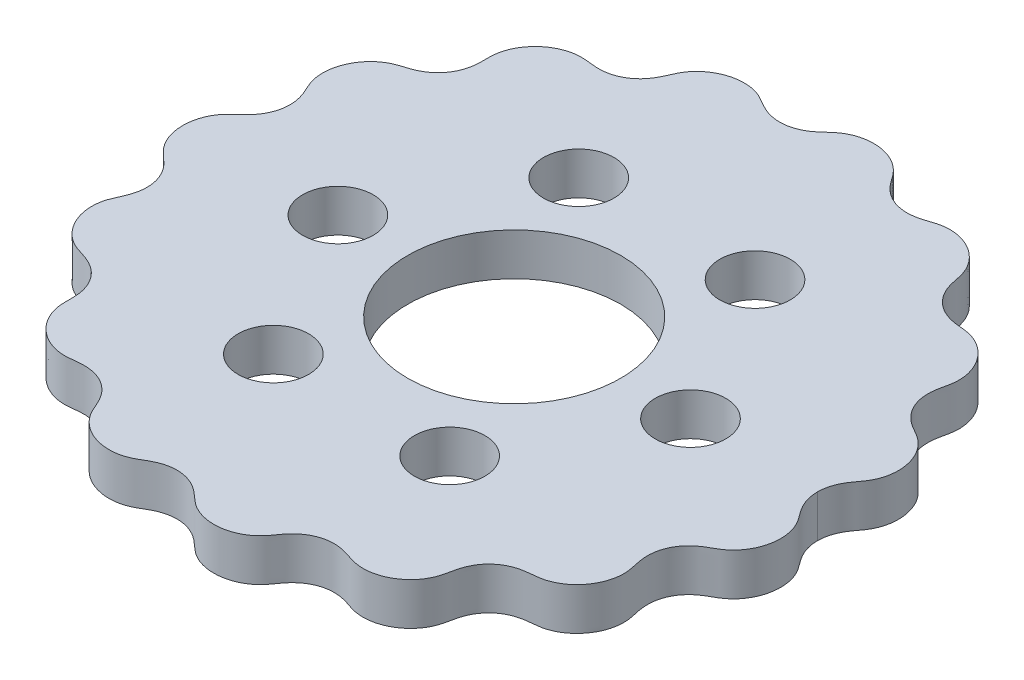
SolidWorks part; units mm, degrees
ref_plane "Alzado" through (0, 0, 0) normal (0, 0, 1) x (1, 0, 0)
ref_plane "Planta" through (0, 0, 0) normal (0, 1, 0) x (1, 0, 0)
ref_plane "Vista lateral" through (0, 0, 0) normal (1, 0, 0) x (0, 0, -1)
sketch "Croquis1" plane through (0, 0, 0) normal (0, 1, 0) x (1, 0, 0)
  line L1 (-23.5, 0) -> (21.5, 0) construction
  circle A8 centre (0, 0) radius 12.5 construction
  circle A9 centre (12.5, 0) radius 2.5
  circle A10 centre (6.25, -10.8253) radius 2.5
  circle A11 centre (-6.25, -10.8253) radius 2.5
  circle A12 centre (-12.5, 0) radius 2.5
  circle A13 centre (-6.25, 10.8253) radius 2.5
  circle A14 centre (6.25, 10.8253) radius 2.5
  circle A15 centre (0, 0) radius 7.55
  spline S0 degree 4 poles (22.3938, 6.206) (22.5098, 6.0505) (22.7166, 5.7207) (22.9456, 5.1865) (23.0698, 4.5223) (23.0708, 3.9491) (22.995, 3.4431) (22.8861, 3.0677) (22.7402, 2.7346) (22.5701, 2.4451) (22.4166, 2.2248) (22.255, 2.0106) (22.0968, 1.7938) (21.9608, 1.5854) (21.8481, 1.3858) (21.7364, 1.1545) (21.6505, 0.933) (21.5836, 0.7054) (21.5367, 0.4716) (21.5147, 0.3126) (21.5037, 0.1561) (21.4997, 0.0354) (21.4998, -0.0402) (21.5033, -0.1416) (21.5104, -0.2506) (21.521, -0.3535) (21.5352, -0.4522) (21.5572, -0.575) (21.5906, -0.7229) (21.6393, -0.8925) (21.7079, -1.082) (21.7887, -1.2667) (21.8884, -1.4605) (22.0086, -1.6616) (22.1498, -1.8685) (22.3094, -2.0824) (22.4687, -2.2964) (22.6163, -2.5189) (22.7773, -2.8114) (22.9505, -3.2395) (23.0755, -3.8173) (23.0785, -4.5347) (22.9117, -5.2906) (22.61, -5.9374) (22.2185, -6.4567) (21.7772, -6.8519) (21.3209, -7.1251) (20.8, -7.4026) (20.2753, -7.7948) (19.8063, -8.3446) (19.475, -9.0614) (19.3598, -9.7832) (19.4098, -10.4522) (19.5346, -10.9747) (19.6222, -11.3739) (19.6633, -11.7809) (19.6552, -12.251) (19.5391, -12.8416) (19.2523, -13.5076) (18.7937, -14.1364) (18.2622, -14.6034) (17.7101, -14.9167) (17.1699, -15.1) (16.67, -15.1754) (16.1916, -15.2048) (15.7411, -15.2785) (15.3268, -15.3998) (14.9543, -15.5661) (14.5264, -15.8332) (14.0827, -16.2428) (13.7242, -16.7761) (13.514, -17.344) (13.4123, -17.8049) (13.3351, -18.2081) (13.2359, -18.6074) (13.025, -19.1081) (12.6416, -19.6627) (12.1028, -20.1652) (11.4122, -20.5639) (10.7076, -20.7793) (10.0356, -20.834) (9.4966, -20.7664) (9.1011, -20.6526) (8.7134, -20.5178) (8.2633, -20.3754) (7.6664, -20.2735) (7.0253, -20.3174) (6.4487, -20.4968) (6.0035, -20.7338) (5.6732, -20.9733) (5.361, -21.2715) (5.0719, -21.6247) (4.8073, -22.0244) (4.4921, -22.4196) (4.0632, -22.7958) (3.5158, -23.1172) (2.8456, -23.344) (2.0718, -23.4267) (1.3515, -23.3422) (0.7822, -23.1473) (0.3707, -22.9196) (0.0947, -22.7199) (-0.1125, -22.543) (-0.3613, -22.3108) (-0.71, -21.9972) (-1.2072, -21.6575) (-1.8903, -21.3967) (-2.6764, -21.325) (-3.3872, -21.4564) (-3.9891, -21.7146) (-4.49, -22.027) (-4.9546, -22.2856) (-5.5176, -22.4702) (-6.163, -22.5495) (-6.8743, -22.4875) (-7.6119, -22.2539) (-8.2323, -21.8928) (-8.7188, -21.4502) (-9.0744, -20.9697) (-9.3045, -20.4864) (-9.5278, -19.9281) (-9.8701, -19.3468) (-10.3865, -18.8074) (-11.0945, -18.3987) (-11.8197, -18.2212) (-12.4943, -18.2154) (-13.0895, -18.3011) (-13.623, -18.3435) (-14.217, -18.2758) (-14.8436, -18.0758) (-15.4665, -17.719) (-16.0376, -17.197) (-16.447, -16.612) (-16.701, -16.0135) (-16.8226, -15.4336) (-16.8309, -14.902) (-16.8108, -14.312) (-16.8881, -13.6616) (-17.1298, -12.9803) (-17.5849, -12.3353) (-18.1524, -11.8742) (-18.6951, -11.6135) (-19.1411, -11.4683) (-19.4666, -11.3689) (-19.7233, -11.2779) (-20.0342, -11.1388) (-20.4373, -10.8962) (-20.8907, -10.5007) (-21.3241, -9.9191) (-21.6393, -9.2077) (-21.778, -8.5138) (-21.7733, -7.8791) (-21.6621, -7.3195) (-21.4771, -6.849) (-21.2186, -6.3289) (-21.0011, -5.7035) (-20.9214, -4.968) (-21.0454, -4.2657) (-21.2856, -3.7121) (-21.5436, -3.3243) (-21.7592, -3.0674) (-21.974, -2.8515) (-22.1775, -2.6683) (-22.3844, -2.489) (-22.5845, -2.3019) (-22.7693, -2.0995) (-22.9352, -1.8813) (-23.0967, -1.6229) (-23.2446, -1.3222) (-23.3437, -1.0477) (-23.4069, -0.8089) (-23.4413, -0.6387) (-23.4581, -0.5412) (-23.4757, -0.42) (-23.4911, -0.2795) (-23.5008, -0.0674) (-23.501, 0.0617) (-23.4905, 0.2958) (-23.4696, 0.4722) (-23.4384, 0.6634) (-23.3968, 0.8485) (-23.3447, 1.0319) (-23.2823, 1.2119) (-23.2033, 1.4023) (-23.1053, 1.6016) (-22.952, 1.8603) (-22.7243, 2.166) (-22.4073, 2.4773) (-22.0362, 2.7842) (-21.7134, 3.1099) (-21.3864, 3.5349) (-21.0986, 4.0919) (-20.9508, 4.7107) (-20.9589, 5.3479) (-21.0451, 5.768) (-21.1059, 5.9731) (-21.1402, 6.0744) knots 0 0 0 0 0 0.008384 0.016767 0.0249 0.028966 0.033032 0.038829 0.041728 0.044627 0.047525 0.050424 0.053322 0.056221 0.05827 0.060319 0.064418 0.066467 0.068516 0.070566 0.07159 0.072615 0.073703 0.074791 0.075879 0.076967 0.078055 0.079143 0.081319 0.083495 0.085672 0.087848 0.090024 0.092906 0.095787 0.098669 0.101551 0.104433 0.107315 0.113078 0.12144 0.129802 0.138039 0.146276 0.152005 0.157733 0.163462 0.169191 0.177517 0.185843 0.194348 0.202854 0.208734 0.214615 0.217555 0.220495 0.226376 0.23487 0.243365 0.251552 0.25974 0.265182 0.270624 0.276066 0.281508 0.285899 0.29029 0.294681 0.299071 0.307626 0.316181 0.322096 0.325053 0.328011 0.333925 0.33984 0.348384 0.356927 0.365471 0.374015 0.37993 0.385844 0.388802 0.391759 0.397674 0.406229 0.414784 0.419174 0.423565 0.427956 0.432347 0.437789 0.443231 0.448673 0.454115 0.462303 0.47049 0.478985 0.487479 0.49336 0.4963 0.49924 0.502181 0.505121 0.511001 0.519507 0.528012 0.536338 0.544664 0.550393 0.556122 0.56185 0.567579 0.575816 0.584053 0.592415 0.600777 0.60654 0.612304 0.618068 0.623831 0.632536 0.64124 0.649944 0.658649 0.664412 0.670176 0.67594 0.681703 0.690065 0.698427 0.706664 0.714901 0.72063 0.726358 0.732087 0.737816 0.746142 0.754468 0.762973 0.771479 0.777359 0.780299 0.78324 0.78618 0.78912 0.795001 0.803495 0.81199 0.820177 0.828365 0.833807 0.839249 0.844691 0.850133 0.858915 0.867696 0.876251 0.880529 0.884806 0.887763 0.890721 0.893678 0.896636 0.899593 0.90255 0.905508 0.908465 0.912737 0.917009 0.918077 0.919145 0.920213 0.921281 0.923416 0.925552 0.927609 0.929666 0.931723 0.93378 0.935836 0.937893 0.93995 0.942007 0.944741 0.947474 0.952942 0.95841 0.963877 0.968289 0.972701 0.981525 0.990762 0.995381 1 1 1 1 1 construction
  spline S1 degree 4 poles (21.5, 0) (21.5, -0.0215) (21.5006, -0.0644) (21.5033, -0.1416) (21.5104, -0.2506) (21.521, -0.3535) (21.5352, -0.4522) (21.5572, -0.575) (21.5906, -0.7229) (21.6393, -0.8925) (21.7079, -1.082) (21.7887, -1.2667) (21.8884, -1.4605) (22.0086, -1.6616) (22.1498, -1.8685) (22.3094, -2.0824) (22.4687, -2.2964) (22.6163, -2.5189) (22.7773, -2.8114) (22.9505, -3.2395) (23.0755, -3.8173) (23.0785, -4.5347) (22.9117, -5.2906) (22.61, -5.9374) (22.2185, -6.4567) (21.7772, -6.8519) (21.3209, -7.1251) (20.8, -7.4026) (20.2753, -7.7948) (19.8063, -8.3446) (19.475, -9.0614) (19.3598, -9.7832) (19.4098, -10.4522) (19.5346, -10.9747) (19.6222, -11.3739) (19.6633, -11.7809) (19.6552, -12.251) (19.5391, -12.8416) (19.2523, -13.5076) (18.7937, -14.1364) (18.2622, -14.6034) (17.7101, -14.9167) (17.1699, -15.1) (16.67, -15.1754) (16.1916, -15.2048) (15.7411, -15.2785) (15.3268, -15.3998) (14.9543, -15.5661) (14.5264, -15.8332) (14.0827, -16.2428) (13.7242, -16.7761) (13.514, -17.344) (13.4123, -17.8049) (13.3351, -18.2081) (13.2359, -18.6074) (13.025, -19.1081) (12.6416, -19.6627) (12.1028, -20.1652) (11.4122, -20.5639) (10.7076, -20.7793) (10.0356, -20.834) (9.4966, -20.7664) (9.1011, -20.6526) (8.7134, -20.5178) (8.2633, -20.3754) (7.6664, -20.2735) (7.0253, -20.3174) (6.4487, -20.4968) (6.0035, -20.7338) (5.6732, -20.9733) (5.361, -21.2715) (5.0719, -21.6247) (4.8073, -22.0244) (4.4921, -22.4196) (4.0632, -22.7958) (3.5158, -23.1172) (2.8456, -23.344) (2.0718, -23.4267) (1.3515, -23.3422) (0.7822, -23.1473) (0.3707, -22.9196) (0.0947, -22.7199) (-0.1125, -22.543) (-0.3613, -22.3108) (-0.71, -21.9972) (-1.2072, -21.6575) (-1.8903, -21.3967) (-2.6764, -21.325) (-3.3872, -21.4564) (-3.9891, -21.7146) (-4.49, -22.027) (-4.9546, -22.2856) (-5.5176, -22.4702) (-6.163, -22.5495) (-6.8743, -22.4875) (-7.6119, -22.2539) (-8.2323, -21.8928) (-8.7188, -21.4502) (-9.0744, -20.9697) (-9.3045, -20.4864) (-9.5278, -19.9281) (-9.8701, -19.3468) (-10.3865, -18.8074) (-11.0945, -18.3987) (-11.8197, -18.2212) (-12.4943, -18.2154) (-13.0895, -18.3011) (-13.623, -18.3435) (-14.217, -18.2758) (-14.8436, -18.0758) (-15.4665, -17.719) (-16.0376, -17.197) (-16.447, -16.612) (-16.701, -16.0135) (-16.8226, -15.4336) (-16.8309, -14.902) (-16.8108, -14.312) (-16.8881, -13.6616) (-17.1298, -12.9803) (-17.5849, -12.3353) (-18.1524, -11.8742) (-18.6951, -11.6135) (-19.1411, -11.4683) (-19.4666, -11.3689) (-19.7233, -11.2779) (-20.0342, -11.1388) (-20.4373, -10.8962) (-20.8907, -10.5007) (-21.3241, -9.9191) (-21.6393, -9.2077) (-21.778, -8.5138) (-21.7733, -7.8791) (-21.6621, -7.3195) (-21.4771, -6.849) (-21.2186, -6.3289) (-21.0011, -5.7035) (-20.9214, -4.968) (-21.0454, -4.2657) (-21.2856, -3.7121) (-21.5436, -3.3243) (-21.7592, -3.0674) (-21.974, -2.8515) (-22.1775, -2.6683) (-22.3844, -2.489) (-22.5845, -2.3019) (-22.7693, -2.0995) (-22.9352, -1.8813) (-23.0967, -1.6229) (-23.2446, -1.3222) (-23.3437, -1.0477) (-23.4069, -0.8089) (-23.4413, -0.6387) (-23.4581, -0.5412) (-23.4757, -0.42) (-23.4911, -0.2795) (-23.4981, -0.1264) (-23.5, -0.0422) (-23.5, 0) knots 0.072615 0.072615 0.072615 0.072615 0.072615 0.073703 0.074791 0.075879 0.076967 0.078055 0.079143 0.081319 0.083495 0.085672 0.087848 0.090024 0.092906 0.095787 0.098669 0.101551 0.104433 0.107315 0.113078 0.12144 0.129802 0.138039 0.146276 0.152005 0.157733 0.163462 0.169191 0.177517 0.185843 0.194348 0.202854 0.208734 0.214615 0.217555 0.220495 0.226376 0.23487 0.243365 0.251552 0.25974 0.265182 0.270624 0.276066 0.281508 0.285899 0.29029 0.294681 0.299071 0.307626 0.316181 0.322096 0.325053 0.328011 0.333925 0.33984 0.348384 0.356927 0.365471 0.374015 0.37993 0.385844 0.388802 0.391759 0.397674 0.406229 0.414784 0.419174 0.423565 0.427956 0.432347 0.437789 0.443231 0.448673 0.454115 0.462303 0.47049 0.478985 0.487479 0.49336 0.4963 0.49924 0.502181 0.505121 0.511001 0.519507 0.528012 0.536338 0.544664 0.550393 0.556122 0.56185 0.567579 0.575816 0.584053 0.592415 0.600777 0.60654 0.612304 0.618068 0.623831 0.632536 0.64124 0.649944 0.658649 0.664412 0.670176 0.67594 0.681703 0.690065 0.698427 0.706664 0.714901 0.72063 0.726358 0.732087 0.737816 0.746142 0.754468 0.762973 0.771479 0.777359 0.780299 0.78324 0.78618 0.78912 0.795001 0.803495 0.81199 0.820177 0.828365 0.833807 0.839249 0.844691 0.850133 0.858915 0.867696 0.876251 0.880529 0.884806 0.887763 0.890721 0.893678 0.896636 0.899593 0.90255 0.905508 0.908465 0.912737 0.917009 0.918077 0.919145 0.920213 0.921281 0.923416 0.925552 0.925552 0.925552 0.925552 0.925552
  spline S2 degree 4 poles (21.5, 0) (21.5, 0.0215) (21.5006, 0.0644) (21.5033, 0.1416) (21.5104, 0.2506) (21.521, 0.3535) (21.5352, 0.4522) (21.5572, 0.575) (21.5906, 0.7229) (21.6393, 0.8925) (21.7079, 1.082) (21.7887, 1.2667) (21.8884, 1.4605) (22.0086, 1.6616) (22.1498, 1.8685) (22.3094, 2.0824) (22.4687, 2.2964) (22.6163, 2.5189) (22.7773, 2.8114) (22.9505, 3.2395) (23.0755, 3.8173) (23.0785, 4.5347) (22.9117, 5.2906) (22.61, 5.9374) (22.2185, 6.4567) (21.7772, 6.8519) (21.3209, 7.1251) (20.8, 7.4026) (20.2753, 7.7948) (19.8063, 8.3446) (19.475, 9.0614) (19.3598, 9.7832) (19.4098, 10.4522) (19.5346, 10.9747) (19.6222, 11.3739) (19.6633, 11.7809) (19.6552, 12.251) (19.5391, 12.8416) (19.2523, 13.5076) (18.7937, 14.1364) (18.2622, 14.6034) (17.7101, 14.9167) (17.1699, 15.1) (16.67, 15.1754) (16.1916, 15.2048) (15.7411, 15.2785) (15.3268, 15.3998) (14.9543, 15.5661) (14.5264, 15.8332) (14.0827, 16.2428) (13.7242, 16.7761) (13.514, 17.344) (13.4123, 17.8049) (13.3351, 18.2081) (13.2359, 18.6074) (13.025, 19.1081) (12.6416, 19.6627) (12.1028, 20.1652) (11.4122, 20.5639) (10.7076, 20.7793) (10.0356, 20.834) (9.4966, 20.7664) (9.1011, 20.6526) (8.7134, 20.5178) (8.2633, 20.3754) (7.6664, 20.2735) (7.0253, 20.3174) (6.4487, 20.4968) (6.0035, 20.7338) (5.6732, 20.9733) (5.361, 21.2715) (5.0719, 21.6247) (4.8073, 22.0244) (4.4921, 22.4196) (4.0632, 22.7958) (3.5158, 23.1172) (2.8456, 23.344) (2.0718, 23.4267) (1.3515, 23.3422) (0.7822, 23.1473) (0.3707, 22.9196) (0.0947, 22.7199) (-0.1125, 22.543) (-0.3613, 22.3108) (-0.71, 21.9972) (-1.2072, 21.6575) (-1.8903, 21.3967) (-2.6764, 21.325) (-3.3872, 21.4564) (-3.9891, 21.7146) (-4.49, 22.027) (-4.9546, 22.2856) (-5.5176, 22.4702) (-6.163, 22.5495) (-6.8743, 22.4875) (-7.6119, 22.2539) (-8.2323, 21.8928) (-8.7188, 21.4502) (-9.0744, 20.9697) (-9.3045, 20.4864) (-9.5278, 19.9281) (-9.8701, 19.3468) (-10.3865, 18.8074) (-11.0945, 18.3987) (-11.8197, 18.2212) (-12.4943, 18.2154) (-13.0895, 18.3011) (-13.623, 18.3435) (-14.217, 18.2758) (-14.8436, 18.0758) (-15.4665, 17.719) (-16.0376, 17.197) (-16.447, 16.612) (-16.701, 16.0135) (-16.8226, 15.4336) (-16.8309, 14.902) (-16.8108, 14.312) (-16.8881, 13.6616) (-17.1298, 12.9803) (-17.5849, 12.3353) (-18.1524, 11.8742) (-18.6951, 11.6135) (-19.1411, 11.4683) (-19.4666, 11.3689) (-19.7233, 11.2779) (-20.0342, 11.1388) (-20.4373, 10.8962) (-20.8907, 10.5007) (-21.3241, 9.9191) (-21.6393, 9.2077) (-21.778, 8.5138) (-21.7733, 7.8791) (-21.6621, 7.3195) (-21.4771, 6.849) (-21.2186, 6.3289) (-21.0011, 5.7035) (-20.9214, 4.968) (-21.0454, 4.2657) (-21.2856, 3.7121) (-21.5436, 3.3243) (-21.7592, 3.0674) (-21.974, 2.8515) (-22.1775, 2.6683) (-22.3844, 2.489) (-22.5845, 2.3019) (-22.7693, 2.0995) (-22.9352, 1.8813) (-23.0967, 1.6229) (-23.2446, 1.3222) (-23.3437, 1.0477) (-23.4069, 0.8089) (-23.4413, 0.6387) (-23.4581, 0.5412) (-23.4757, 0.42) (-23.4911, 0.2795) (-23.4981, 0.1264) (-23.5, 0.0422) (-23.5, 0) knots 0.072615 0.072615 0.072615 0.072615 0.072615 0.073703 0.074791 0.075879 0.076967 0.078055 0.079143 0.081319 0.083495 0.085672 0.087848 0.090024 0.092906 0.095787 0.098669 0.101551 0.104433 0.107315 0.113078 0.12144 0.129802 0.138039 0.146276 0.152005 0.157733 0.163462 0.169191 0.177517 0.185843 0.194348 0.202854 0.208734 0.214615 0.217555 0.220495 0.226376 0.23487 0.243365 0.251552 0.25974 0.265182 0.270624 0.276066 0.281508 0.285899 0.29029 0.294681 0.299071 0.307626 0.316181 0.322096 0.325053 0.328011 0.333925 0.33984 0.348384 0.356927 0.365471 0.374015 0.37993 0.385844 0.388802 0.391759 0.397674 0.406229 0.414784 0.419174 0.423565 0.427956 0.432347 0.437789 0.443231 0.448673 0.454115 0.462303 0.47049 0.478985 0.487479 0.49336 0.4963 0.49924 0.502181 0.505121 0.511001 0.519507 0.528012 0.536338 0.544664 0.550393 0.556122 0.56185 0.567579 0.575816 0.584053 0.592415 0.600777 0.60654 0.612304 0.618068 0.623831 0.632536 0.64124 0.649944 0.658649 0.664412 0.670176 0.67594 0.681703 0.690065 0.698427 0.706664 0.714901 0.72063 0.726358 0.732087 0.737816 0.746142 0.754468 0.762973 0.771479 0.777359 0.780299 0.78324 0.78618 0.78912 0.795001 0.803495 0.81199 0.820177 0.828365 0.833807 0.839249 0.844691 0.850133 0.858915 0.867696 0.876251 0.880529 0.884806 0.887763 0.890721 0.893678 0.896636 0.899593 0.90255 0.905508 0.908465 0.912737 0.917009 0.918077 0.919145 0.920213 0.921281 0.923416 0.925552 0.925552 0.925552 0.925552 0.925552
  point P22 (0, 0)
  dimension "D1" = 5
  dimension "D2" = 25
  dimension "D3" = 15.1
extrude "Saliente-Extruir1" add sketch "Croquis1" along normal blind 3
